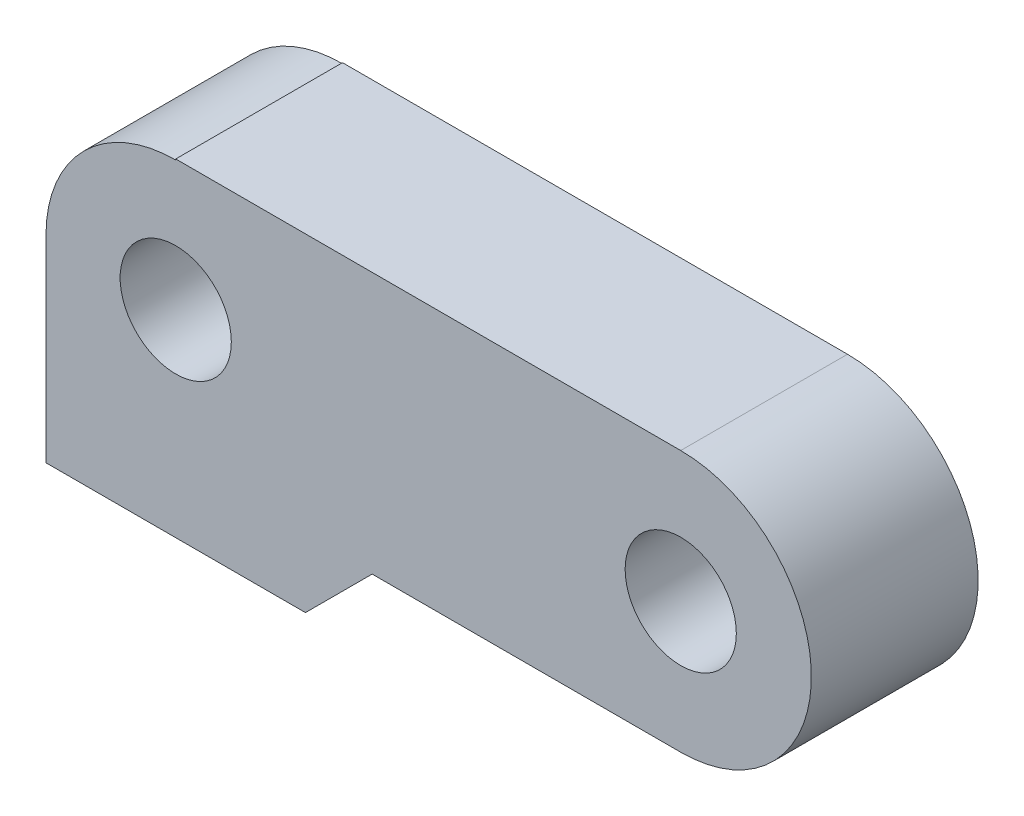
SolidWorks part; units mm, degrees
ref_plane "Ön Düzlem" through (0, 0, 0) normal (0, 0, 1) x (1, 0, 0)
ref_plane "Üst Düzlem" through (0, 0, 0) normal (0, 1, 0) x (1, 0, 0)
ref_plane "Sağ Düzlem" through (0, 0, 0) normal (1, 0, 0) x (0, 0, -1)
sketch "Sketch1" plane through (0, 0, 0) normal (0, 0, 1) x (1, 0, 0)
  line L1 (-41.5, -17.7) -> (41.5, -17.7)
  line L2 (-41.5, -17.7) -> (-41.5, 17.7)
  line L3 (-41.5, 17.7) -> (41.5, 17.7)
  line L4 (41.5, -17.7) -> (41.5, 17.7)
  line L5 (-41.5, -17.7) -> (41.5, 17.7) construction
  line L6 (-41.5, 17.7) -> (41.5, -17.7) construction
  circle A0 centre (-27.5, 3.6) radius 6
  circle A1 centre (27, 3.6) radius 6
  point P0 (0, 0)
  dimension "D6" = 12
  dimension "D7" = 12
  dimension "D1" = 14
  dimension "D2" = 54.5
  dimension "D3" = 21.3
  dimension "D4" = 35.4
  dimension "D5" = 83
extrude "Boss-Extrude1" add sketch "Sketch1" along normal blind 18
sketch "Sketch2" plane through (0, 0, 18) normal (0, 0, 1) x (1, 0, 0)
  line L0 (27, -10.5) -> (-6.3, -10.5)
  line L1 (-6.3, -10.5) -> (-13.5, -17.7)
  line L2 (-41.5, -17.7) -> (41.5, -17.7) construction
  line L3 (-13.5, -17.7) -> (-41.5, -17.7)
  line L4 (-41.5, -17.7) -> (-41.5, -37.1081)
  line L5 (-41.5, -37.1081) -> (58.0649, -37.1081)
  line L6 (58.0649, -37.1081) -> (58.0649, 31.4832)
  line L7 (58.0649, 31.4832) -> (27, 31.4832)
  line L8 (27, 31.4832) -> (27, 17.7)
  arc A0 (27, -10.5) -> (27, 17.7) centre (27, 3.6) ccw
  dimension "D1" = 28.2
  dimension "D2" = 135
  dimension "D3" = 28
extrude "Cut-Extrude1" cut sketch "Sketch2" against normal through all
sketch "Sketch3" plane through (0, 0, 18) normal (0, 0, 1) x (1, 0, 0)
  line L0 (-27.5, 17.6) -> (-27.5, 27.1418)
  line L1 (-27.5, 27.1418) -> (-58.4763, 27.1418)
  line L2 (-58.4763, 27.1418) -> (-58.4763, 3.6)
  line L3 (-58.4763, 3.6) -> (-41.5, 3.6)
  arc A0 (-27.5, 17.6) -> (-41.5, 3.6) centre (-27.5, 3.6) ccw
extrude "Cut-Extrude2" cut sketch "Sketch3" against normal through all
sketch "Sketch4" plane through (0, 0, 0) normal (0, 0, -1) x (-1, 0, 0)
  circle A0 centre (-27, 3.6) radius 10
  dimension "D1" = 20
extrude "Cut-Extrude3" cut sketch "Sketch4" against normal blind 5
